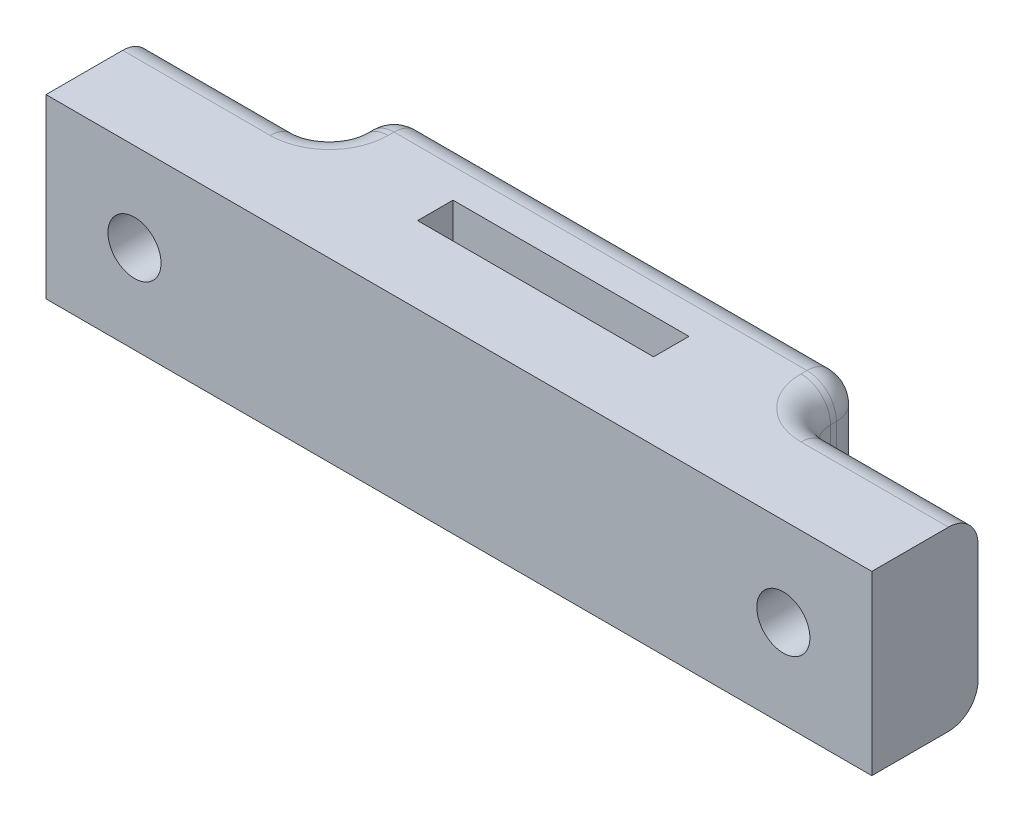
SolidWorks part; units mm, degrees
ref_plane "Front Plane" through (0, 0, 0) normal (0, 0, 1) x (1, 0, 0)
ref_plane "Top Plane" through (0, 0, 0) normal (0, 1, 0) x (1, 0, 0)
ref_plane "Right Plane" through (0, 0, 0) normal (1, 0, 0) x (0, 0, -1)
sketch "Sketch1" plane through (0, 0, 0) normal (0, 1, 0) x (1, 0, 0)
  line L0 (-20, 6.5) -> (20, 6.5)
  line L1 (20, 6.5) -> (20, 1)
  line L2 (20, 1) -> (35, 1)
  line L3 (35, 1) -> (35, -8)
  line L4 (35, -8) -> (-35, -8)
  line L5 (-35, -8) -> (-35, 1)
  line L6 (-35, 1) -> (-20, 1)
  line L7 (-20, 1) -> (-20, 6.5)
  line L9 (-10, 1.5) -> (10, 1.5)
  line L10 (-10, 1.5) -> (-10, -1.5)
  line L11 (-10, -1.5) -> (10, -1.5)
  line L12 (10, 1.5) -> (10, -1.5)
  line L13 (-10, 1.5) -> (10, -1.5) construction
  line L14 (-10, -1.5) -> (10, 1.5) construction
  point P8 (0, 0)
  point P13 (0, 6.5)
  point P14 (10, 0)
  dimension "D1" = 20
  dimension "D2" = 3
  dimension "D3" = 5
  dimension "D4" = 8
  dimension "D5" = 70
  dimension "D6" = 40
  dimension "D7" = 9
extrude "Boss-Extrude1" add sketch "Sketch1" along normal blind 15
sketch "Sketch2" plane through (0, 0, -1) normal (0, 0, -1) x (-1, 0, 0)
  line L0 (-35, 15) -> (-35, 0) construction
  line L1 (-35, 15) -> (-20, 15) construction
  line L2 (0, 8.25) -> (0, -8.25) construction
  point P0 (-27.5, 7.5)
  point P3 (-35, 7.5)
  point P7 (-27.5, 15)
  point P10 (27.5, 7.5)
hole_wizard "CBORE for M4 Hex Socket Head Cap Screw1" positions "3DSketch1" profile "Sketch3" counterbore size "M4" standard "DIN" end condition up to next
sketch3d "3DSketch1"
  point P0 (27.5, 7.5, -1)
  point P3 (-27.5, 7.5, -1)
sketch "Sketch3" plane through (27.5, 7.5, -1) normal (1, 0, 0) x (0, 1, 0)
  line L0 (0, 0) -> (0, 9)
  line L1 (0, 9) -> (2.25, 9)
  line L3 (2.25, 9) -> (2.25, 4.4)
  line L4 (2.25, 4.4) -> (4, 4.4)
  line L5 (4, 4.4) -> (4, 0)
  line L7 (4, 0) -> (0, 0)
  line L11 (0, -6.35) -> (0, 107.95) construction
  dimension "Thru Hole Dia." = 4.5
  dimension "Thru Hole Depth" = 9
  dimension "C'Bore Dia." = 8
  dimension "C'Bore Depth" = 4.4
fillet "Fillet1" radius 2.5 14 edges at (-27.5, 15, -1) (-27.5, 0, -1) (20, 15, -3.75) (27.5, 0, -1) (-20, 7.5, -6.5) (-20, 15, -3.75) (-20, 7.5, -1) (-20, 0, -3.75) (27.5, 15, -1) (0, 0, -6.5) (0, 15, -6.5) (20, 7.5, -6.5) (20, 7.5, -1) (20, 0, -3.75)
